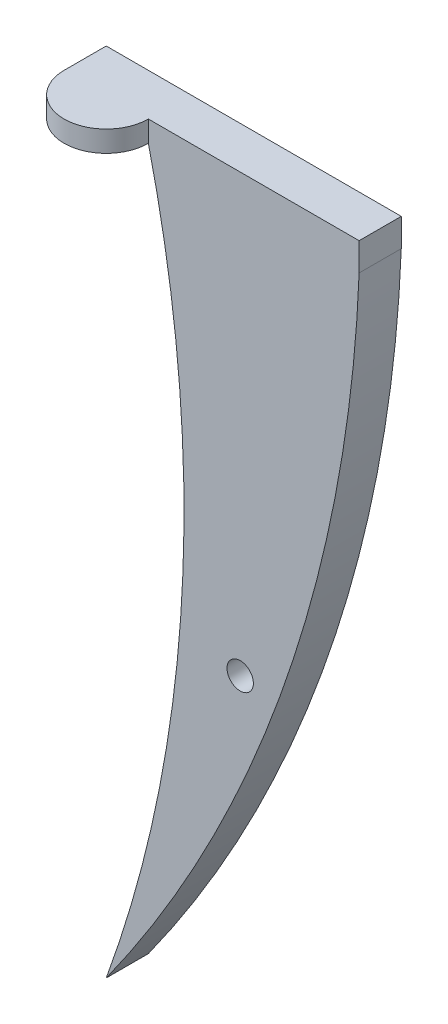
SolidWorks part; units mm, degrees
ref_plane "Front Plane" through (0, 0, 0) normal (0, 0, 1) x (1, 0, 0)
ref_plane "Top Plane" through (0, 0, 0) normal (0, 1, 0) x (1, 0, 0)
ref_plane "Right Plane" through (0, 0, 0) normal (1, 0, 0) x (0, 0, -1)
sketch "Sketch1" plane through (0, 0, 0) normal (0, 1, 0) x (1, 0, 0)
  line L1 (17.78, -2.54) -> (-17.78, -2.54)
  line L2 (17.78, -2.54) -> (17.78, 2.54)
  line L3 (17.78, 2.54) -> (-17.78, 2.54)
  line L4 (-17.78, -2.54) -> (-17.78, 2.54)
  line L5 (17.78, -2.54) -> (-17.78, 2.54) construction
  line L6 (17.78, 2.54) -> (-17.78, -2.54) construction
  point P0 (0, 0)
  dimension "D1" = 5.08
  dimension "D2" = 35.56
extrude "Boss-Extrude1" add sketch "Sketch1" along normal blind 92.202
sketch "Sketch4" plane through (0, 0, 2.54) normal (0, 0, 1) x (1, 0, 0)
  line L1 (-17.78, 92.202) -> (-7.62, 92.202)
  line L2 (-17.78, 92.202) -> (-17.78, 89.662)
  line L3 (-17.78, 89.662) -> (-7.62, 89.662)
  line L4 (-7.62, 92.202) -> (-7.62, 89.662)
  dimension "D1" = 2.54
  dimension "D2" = 10.16
extrude "Boss-Extrude4" add sketch "Sketch4" along normal blind 5.08
sketch "Sketch5" plane through (0, 92.202, 0) normal (0, 1, 0) x (1, 0, 0)
  line L0 (-7.62, -2.54) -> (-17.78, -2.54)
  arc A0 (-17.78, -2.54) -> (-7.62, -2.54) centre (-12.7, -2.54) ccw
  line M1 (-17.78, 2.54) -> (-17.78, -7.62)
  line M2 (-17.78, -7.62) -> (-7.62, -7.62)
  line M3 (-7.62, -7.62) -> (-7.62, -2.54)
extrude "Cut-Extrude1" cut sketch "Sketch5" against normal blind 2.54 contours A0 M1 M2 | A0 M2 M3
sketch "Sketch7" plane through (0, 0, 2.54) normal (0, 0, 1) x (1, 0, 0)
  line L0 (-7.62, 0) -> (-12.7, 0) construction
  line L1 (-7.62, 89.662) -> (17.78, 89.662)
  line L2 (-7.62, 89.662) -> (-17.78, 89.662)
  line L3 (-17.78, 89.662) -> (-17.78, 0)
  line L4 (-17.78, 0) -> (-12.7, 0)
  line L5 (-12.7, 0) -> (17.78, 0)
  line L6 (17.78, 0) -> (17.78, 89.662)
  line L7 (17.78, 92.202) -> (17.78, 0) construction
  arc A0 (-12.7, 0) -> (17.78, 88.8319) centre (-145.6702, 95.2698) ccw
  arc A1 (-12.7, 0) -> (-7.62, 89.662) centre (-159.4741, 53.2907) ccw
  line M5 (-17.78, 0) -> (17.78, 0)
  line M6 (17.78, 0) -> (17.78, 92.202)
  line M8 (-7.62, 89.662) -> (-17.78, 89.662)
  line M9 (-17.78, 89.662) -> (-17.78, 0)
extrude "Cut-Extrude3" cut sketch "Sketch7" against normal through all contours A1 M5 M8 M9 | A0 L5 M5 M6
sketch "Sketch9" plane through (0, 92.202, 0) normal (0, 1, 0) x (1, 0, 0)
  line L0 (-7.62, -2.54) -> (-12.7, -2.54) construction
  circle A0 centre (-12.7, -2.54) radius 1.5875 construction
  dimension "D1" = 3.175
sketch "Sketch13" plane through (0, 0, 2.54) normal (0, 0, 1) x (1, 0, 0)
  circle A2 centre (3.4469, 39.62) radius 1.5875
  dimension "D1" = 3.175
extrude "Cut-Extrude4" cut sketch "Sketch13" against normal through all
equation "\"HEIGHT OF BASE PLATE\"= 2"
equation "\"THICK\"= .2"
equation "\"HOLE SIZE\"= .125"
